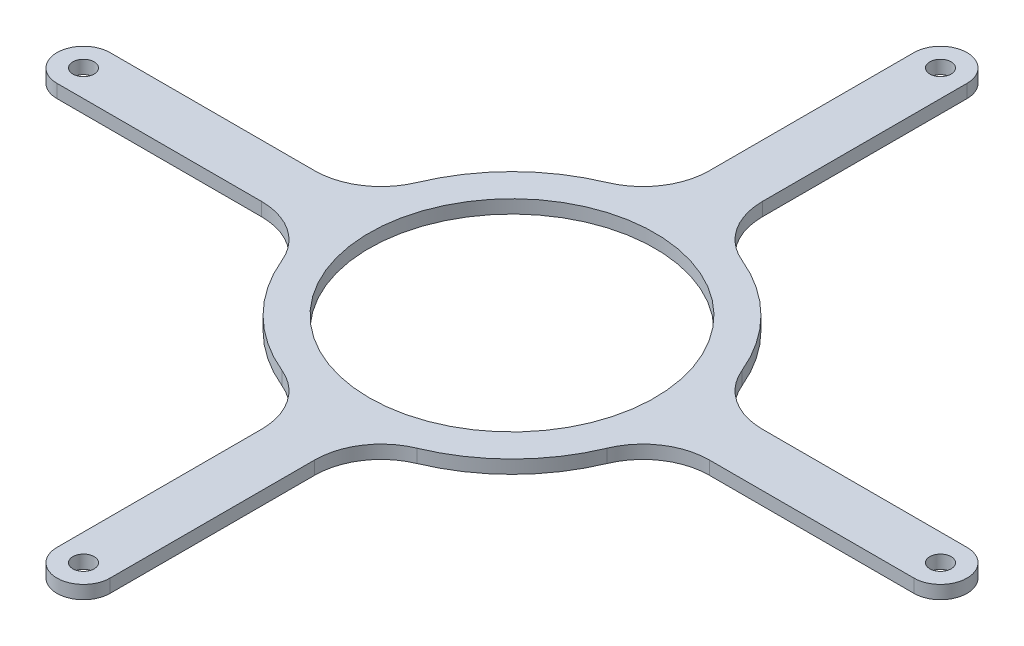
SolidWorks part; units mm, degrees
ref_plane "Front Plane" through (0, 0, 0) normal (0, 0, 1) x (1, 0, 0)
ref_plane "Top Plane" through (0, 0, 0) normal (0, 1, 0) x (1, 0, 0)
ref_plane "Right Plane" through (0, 0, 0) normal (1, 0, 0) x (0, 0, -1)
sketch "Sketch1" plane through (0, 0, 0) normal (0, 1, 0) x (1, 0, 0)
  line L0 (0, 0) -> (0, 64.5) construction
  line L1 (4, 26.1964) -> (4, 64.5)
  line L2 (-4, 26.1964) -> (-4, 64.5)
  line L3 (-4, 0) -> (-4, 64.5) construction
  line L4 (4, 0) -> (4, 64.5) construction
  line L5 (26.1964, -4) -> (64.5, -4)
  line L6 (26.1964, 4) -> (64.5, 4)
  line L7 (0, 0) -> (64.5, 0) construction
  line L8 (-4, -26.1964) -> (-4, -64.5)
  line L9 (4, -26.1964) -> (4, -64.5)
  line L10 (0, 0) -> (0, -64.5) construction
  line L11 (-26.1964, 4) -> (-64.5, 4)
  line L12 (-26.1964, -4) -> (-64.5, -4)
  line L13 (0, 0) -> (-64.5, 0) construction
  circle A0 centre (0, 0) radius 21.5
  arc A1 (-4, 26.1964) -> (-26.1964, 4) centre (0, 0) ccw
  arc A4 (4, 64.5) -> (-4, 64.5) centre (0, 64.5) ccw
  circle A5 centre (0, 64.5) radius 1.6
  arc A6 (64.5, -4) -> (64.5, 4) centre (64.5, 0) ccw
  circle A7 centre (64.5, 0) radius 1.6
  arc A8 (-4, -64.5) -> (4, -64.5) centre (0, -64.5) ccw
  circle A9 centre (0, -64.5) radius 1.6
  arc A10 (-64.5, 4) -> (-64.5, -4) centre (-64.5, 0) ccw
  circle A11 centre (-64.5, 0) radius 1.6
  arc A12 (-26.1964, -4) -> (-4, -26.1964) centre (0, 0) ccw
  arc A13 (26.1964, 4) -> (4, 26.1964) centre (0, 0) ccw
  arc A14 (4, -26.1964) -> (26.1964, -4) centre (0, 0) ccw
  circle A15 centre (0, 64.5) radius 1.5 construction
  circle A16 centre (0, 64.5) radius 1.5 construction
  circle A17 centre (0, 0) radius 23.5 construction
  circle A18 centre (0, 0) radius 23.5 construction
  point P10 (0, 92.0736)
  point P32 (0, 0)
  point P34 (0, 64.9761)
  dimension "D4" = 3.2
  dimension "D5" = 2
  dimension "D6" = 5
  dimension "D1" = 4
  dimension "D2" = 4
  dimension "D3" = 4
extrude "Boss-Extrude1" add sketch "Sketch1" along normal blind 2
fillet "Fillet1" radius 10 8 edges at (26.1964, 1, -4) (26.1964, 1, 4) (4, 1, 26.1964) (-4, 1, 26.1964) (-26.1964, 1, 4) (-4, 1, -26.1964) (4, 1, -26.1964) (-26.1964, 1, -4)
